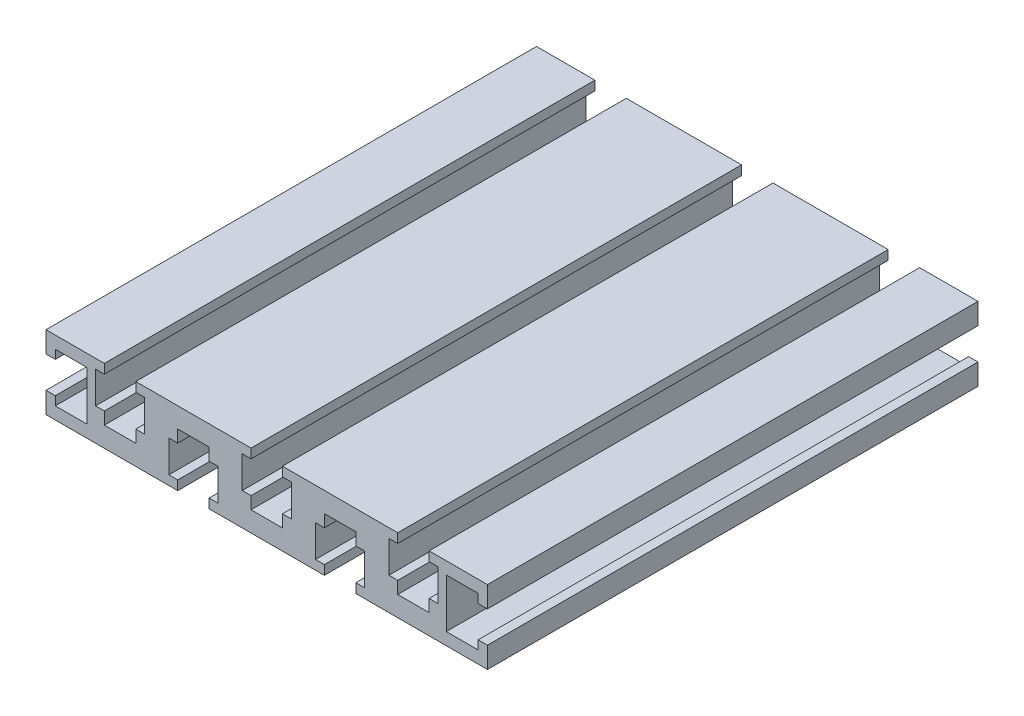
SolidWorks part; units mm, degrees
ref_plane "前视基准面" through (0, 0, 0) normal (0, 0, 1) x (1, 0, 0)
ref_plane "上视基准面" through (0, 0, 0) normal (0, 1, 0) x (1, 0, 0)
ref_plane "右视基准面" through (0, 0, 0) normal (1, 0, 0) x (0, 0, -1)
sketch "草图1" plane through (0, 0, 0) normal (0, 0, 1) x (1, 0, 0)
  line L0 (-44.5744, -2.7458) -> (-44.5744, -7.0458)
  line L1 (-44.5744, -7.0458) -> (-17.7244, -7.0458)
  line L2 (-11.3244, -7.0458) -> (12.1756, -7.0458)
  line L3 (18.5756, -7.0458) -> (45.4256, -7.0458)
  line L4 (45.4256, -7.0458) -> (45.4256, -2.7458)
  line L5 (45.4256, 3.6542) -> (45.4256, 7.9542)
  line L6 (45.4256, 7.9542) -> (33.5256, 7.9542)
  line L7 (27.1256, 7.9542) -> (3.6256, 7.9542)
  line L8 (-2.7744, 7.9542) -> (-26.2744, 7.9542)
  line L9 (-32.6744, 7.9542) -> (-44.5744, 7.9542)
  line L10 (-44.5744, 7.9542) -> (-44.5744, 3.6542)
  line L11 (-44.5744, 3.6542) -> (-42.6744, 3.6542)
  line L12 (-44.5744, -2.7458) -> (-42.6744, -2.7458)
  line L13 (-36.1744, 5.4542) -> (-36.1744, -4.5458)
  line L14 (-42.6744, 5.4542) -> (-42.6744, 3.6542)
  line L15 (-42.6744, -2.7458) -> (-42.6744, -4.5458)
  line L16 (-42.6744, 5.4542) -> (-36.1744, 5.4542)
  line L17 (-42.6744, -4.5458) -> (-36.1744, -4.5458)
  line L18 (45.4256, 3.6542) -> (43.5256, 3.6542)
  line L19 (45.4256, -2.7458) -> (43.5256, -2.7458)
  line L20 (37.0256, 5.4542) -> (37.0256, -4.5458)
  line L21 (43.5256, 5.4542) -> (43.5256, 3.6542)
  line L22 (43.5256, -2.7458) -> (43.5256, -4.5458)
  line L23 (43.5256, 5.4542) -> (37.0256, 5.4542)
  line L24 (43.5256, -4.5458) -> (37.0256, -4.5458)
  line L25 (3.6256, 7.9542) -> (3.6256, 6.0542)
  line L26 (-2.7744, 7.9542) -> (-2.7744, 6.0542)
  line L27 (5.4256, -0.4458) -> (3.6256, -0.4458)
  line L28 (-2.7744, -0.4458) -> (-4.5744, -0.4458)
  line L29 (3.6256, -2.9458) -> (-2.7744, -2.9458)
  line L30 (5.4256, 6.0542) -> (3.6256, 6.0542)
  line L31 (-2.7744, 6.0542) -> (-4.5744, 6.0542)
  line L32 (5.4256, 6.0542) -> (5.4256, -0.4458)
  line L33 (-4.5744, 6.0542) -> (-4.5744, -0.4458)
  line L34 (-2.7744, -0.4458) -> (-2.7744, -2.9458)
  line L35 (3.6256, -0.4458) -> (3.6256, -2.9458)
  line L36 (33.5256, 7.9542) -> (33.5256, 6.0542)
  line L37 (27.1256, 7.9542) -> (27.1256, 6.0542)
  line L38 (35.3256, -0.4458) -> (33.5256, -0.4458)
  line L39 (27.1256, -0.4458) -> (25.3256, -0.4458)
  line L40 (33.5256, -2.9458) -> (27.1256, -2.9458)
  line L41 (35.3256, 6.0542) -> (33.5256, 6.0542)
  line L42 (27.1256, 6.0542) -> (25.3256, 6.0542)
  line L43 (35.3256, 6.0542) -> (35.3256, -0.4458)
  line L44 (25.3256, 6.0542) -> (25.3256, -0.4458)
  line L45 (27.1256, -0.4458) -> (27.1256, -2.9458)
  line L46 (33.5256, -0.4458) -> (33.5256, -2.9458)
  line L47 (-32.6744, 7.9542) -> (-32.6744, 6.0542)
  line L48 (-26.2744, 7.9542) -> (-26.2744, 6.0542)
  line L49 (-34.4744, -0.4458) -> (-32.6744, -0.4458)
  line L50 (-26.2744, -0.4458) -> (-24.4744, -0.4458)
  line L51 (-32.6744, -2.9458) -> (-26.2744, -2.9458)
  line L52 (-34.4744, 6.0542) -> (-32.6744, 6.0542)
  line L53 (-26.2744, 6.0542) -> (-24.4744, 6.0542)
  line L54 (-34.4744, 6.0542) -> (-34.4744, -0.4458)
  line L55 (-24.4744, 6.0542) -> (-24.4744, -0.4458)
  line L56 (-26.2744, -0.4458) -> (-26.2744, -2.9458)
  line L57 (-32.6744, -0.4458) -> (-32.6744, -2.9458)
  line L58 (-17.7244, -7.0458) -> (-17.7244, -5.1458)
  line L59 (-11.3244, -7.0458) -> (-11.3244, -5.1458)
  line L60 (-19.5244, 1.3542) -> (-17.7244, 1.3542)
  line L61 (-11.3244, 1.3542) -> (-9.5244, 1.3542)
  line L62 (-17.7244, 3.8542) -> (-11.3244, 3.8542)
  line L63 (-19.5244, -5.1458) -> (-17.7244, -5.1458)
  line L64 (-11.3244, -5.1458) -> (-9.5244, -5.1458)
  line L65 (-19.5244, -5.1458) -> (-19.5244, 1.3542)
  line L66 (-9.5244, -5.1458) -> (-9.5244, 1.3542)
  line L67 (-11.3244, 1.3542) -> (-11.3244, 3.8542)
  line L68 (-17.7244, 1.3542) -> (-17.7244, 3.8542)
  line L69 (18.5756, -7.0458) -> (18.5756, -5.1458)
  line L70 (12.1756, -7.0458) -> (12.1756, -5.1458)
  line L71 (20.3756, 1.3542) -> (18.5756, 1.3542)
  line L72 (12.1756, 1.3542) -> (10.3756, 1.3542)
  line L73 (18.5756, 3.8542) -> (12.1756, 3.8542)
  line L74 (20.3756, -5.1458) -> (18.5756, -5.1458)
  line L75 (12.1756, -5.1458) -> (10.3756, -5.1458)
  line L76 (20.3756, -5.1458) -> (20.3756, 1.3542)
  line L77 (10.3756, -5.1458) -> (10.3756, 1.3542)
  line L78 (12.1756, 1.3542) -> (12.1756, 3.8542)
  line L79 (18.5756, 1.3542) -> (18.5756, 3.8542)
extrude "凸台-拉伸1" add sketch "草图1" along normal blind 100
